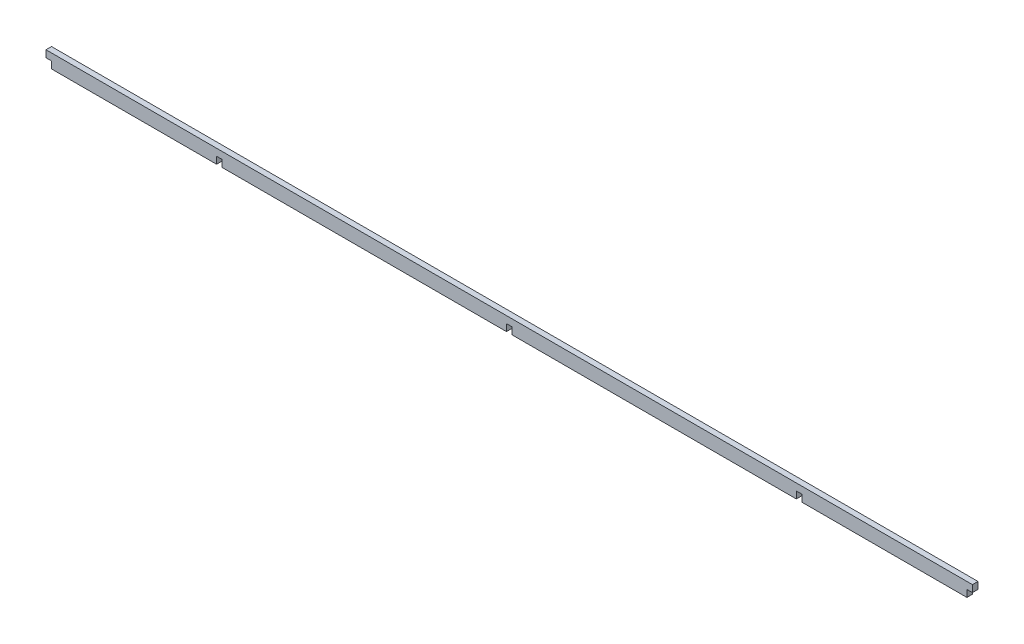
SolidWorks part; units mm, degrees
ref_plane "Front Plane" through (0, 0, 0) normal (0, 0, 1) x (1, 0, 0)
ref_plane "Top Plane" through (0, 0, 0) normal (0, 1, 0) x (1, 0, 0)
ref_plane "Right Plane" through (0, 0, 0) normal (1, 0, 0) x (0, 0, -1)
sketch "Sketch1" plane through (0, 0, 0) normal (0, 0, 1) x (1, 0, 0)
  line L0 (-5, 0) -> (5, 0)
  line L1 (-835, 12.5) -> (835, 12.5)
  line L2 (-835, 12.5) -> (-835, -12.5)
  line L3 (-835, -12.5) -> (-5, -12.5)
  line L4 (835, 12.5) -> (835, -12.5)
  line L5 (-835, 12.5) -> (835, -12.5) construction
  line L6 (-835, -12.5) -> (835, 12.5) construction
  line L7 (5, 0) -> (5, -12.5)
  line L8 (-5, 0) -> (-5, -12.5)
  line L9 (5, -12.5) -> (835, -12.5)
  line L10 (0, 0) -> (0, 14.2959) construction
  line L11 (-835, 0) -> (-825, 0)
  line L12 (-825, 0) -> (-825, -12.5)
  line L13 (-517.5, 0) -> (-517.5, -12.5)
  line L14 (-527.5, 0) -> (-517.5, 0)
  line L15 (835, 0) -> (825, 0)
  line L16 (-527.5, 0) -> (-527.5, -20.6155)
  line L17 (-527.5, 20) -> (-527.5, 12.5145) [skipped]
  line L18 (527.5, 0) -> (527.5, -20.6155)
  line L19 (527.5, 0) -> (517.5, 0)
  line L20 (517.5, 0) -> (517.5, -12.5)
  line L21 (825, 0) -> (825, -12.5)
  point P0 (0, 0)
  point P9 (0, 0)
  dimension "D1" = 25
  dimension "D2" = 1670
  dimension "D3" = 10
  dimension "D4" = 0
  dimension "D5" = 12.5
  dimension "D6" = 10
  dimension "D7" = 2
extrude "Boss-Extrude1" add sketch "Sketch1" along normal blind 10 contours L21 L15 L4 L1 L2 L11 L12 L3 L16 L14 L13 L8 L0 L7 L9 L20 L19 L18
